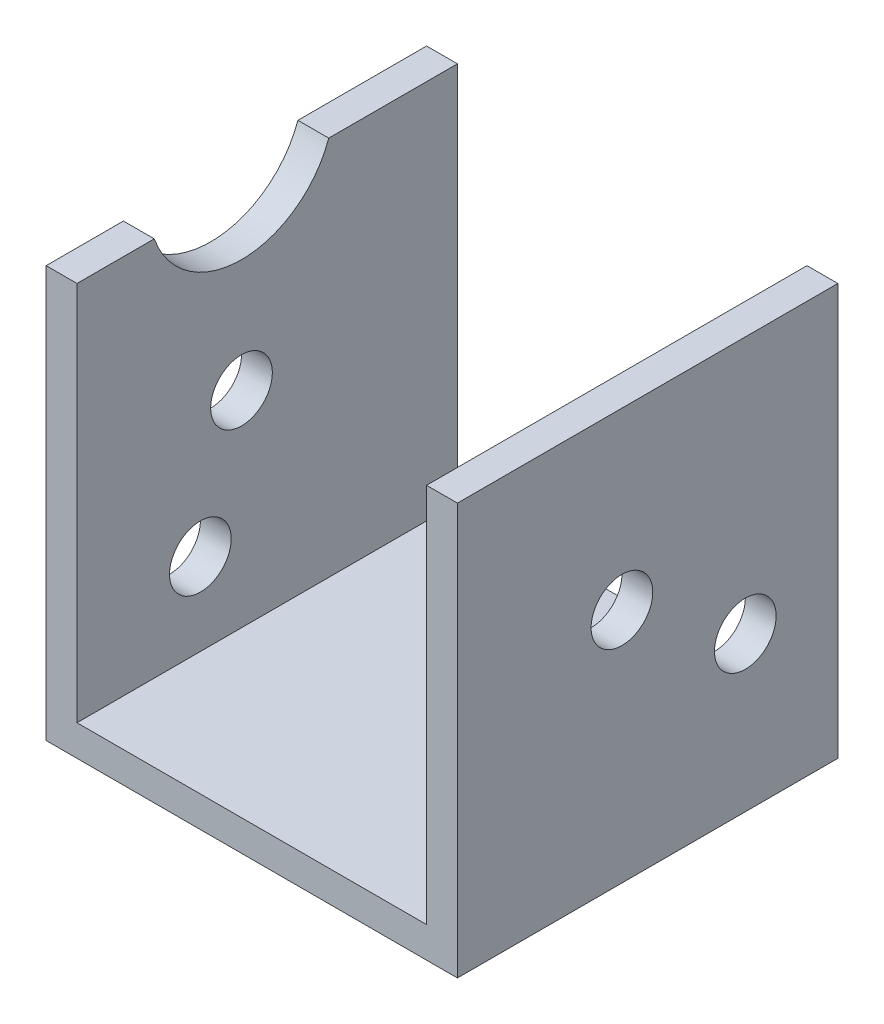
SolidWorks part; units mm, degrees
ref_plane "Plan de face" through (0, 0, 0) normal (0, 0, 1) x (1, 0, 0)
ref_plane "Plan de dessus" through (0, 0, 0) normal (0, 1, 0) x (1, 0, 0)
ref_plane "Plan de droite" through (0, 0, 0) normal (1, 0, 0) x (0, 0, -1)
sketch "Esquisse1" plane through (0, 0, 0) normal (0, 0, 1) x (1, 0, 0)
  line L0 (-16.6363, 18.6356) -> (-16.6363, -1.3644)
  line L1 (-16.6363, -1.3644) -> (3.3637, -1.3644)
  line L2 (3.3637, -1.3644) -> (3.3637, 18.6356)
  line L3 (3.3637, 18.6356) -> (1.8637, 18.6356)
  line L4 (1.8637, 18.6356) -> (1.8637, 0.1356)
  line L5 (1.8637, 0.1356) -> (-15.1363, 0.1356)
  line L6 (-15.1363, 0.1356) -> (-15.1363, 18.6356)
  line L7 (-15.1363, 18.6356) -> (-16.6363, 18.6356)
  dimension "D1" = 1.5
  dimension "D2" = 1.5
  dimension "D3" = 1.5
  dimension "D4" = 20
  dimension "D5" = 20
  dimension "D6" = 20
extrude "Extrusion1" add sketch "Esquisse1" along normal blind 18.5
sketch "Esquisse2" plane through (3.3637, 0, 0) normal (1, 0, 0) x (0, 0, -1)
  line L0 (-18.5, -1.3644) -> (0, -1.3644) construction
  line L1 (0, 18.6356) -> (0, -1.3644) construction
  circle A0 centre (-4.5, 6.1356) radius 1.5
  dimension "D1" = 7.5
  dimension "D2" = 4.5
extrude "Extrusion2" cut sketch "Esquisse2" against normal blind 5
sketch "Esquisse3" plane through (-16.6363, 0, 0) normal (-1, 0, 0) x (0, 0, 1)
  line L0 (18.5, 18.6356) -> (0, 18.6356) construction
  line L1 (18.5, -1.3644) -> (0, -1.3644) construction
  line L2 (18.5, 18.6356) -> (18.5, -1.3644) construction
  circle A0 centre (10.5, 20.1356) radius 4.5
  circle A1 centre (12.5, 4.1356) radius 1.5
  point P12 (18.5, 14.1843)
  dimension "D1" = 5.5
  dimension "D3" = 6
  dimension "D2" = 1.5
  dimension "D4" = 8
extrude "Extrusion3" cut sketch "Esquisse3" against normal blind 5
sketch "Esquisse5" plane through (-16.6363, 0, 0) normal (-1, 0, 0) x (0, 0, 1)
  line L0 (18.5, 18.6356) -> (18.5, -1.3644) construction
  line L1 (18.5, -1.3644) -> (0, -1.3644) construction
  circle A0 centre (10.5, 10.1356) radius 1.5
  dimension "D1" = 8
  dimension "D2" = 11.5
extrude "Extrusion4" cut sketch "Esquisse5" against normal through all
